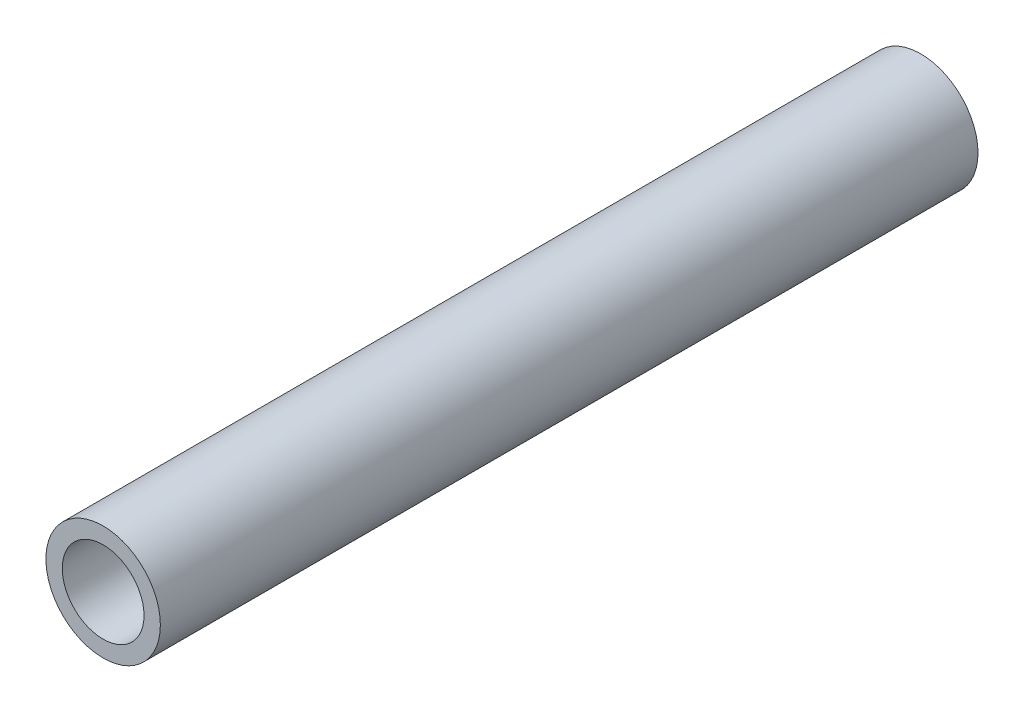
SolidWorks part; units mm, degrees
ref_plane "Plan de face" through (0, 0, 0) normal (0, 0, 1) x (1, 0, 0)
ref_plane "Plan de dessus" through (0, 0, 0) normal (0, 1, 0) x (1, 0, 0)
ref_plane "Plan de droite" through (0, 0, 0) normal (1, 0, 0) x (0, 0, -1)
sketch "Esquisse1" plane through (0, 0, 0) normal (0, 0, 1) x (1, 0, 0)
  circle A0 centre (0, 0) radius 2.5
  circle A1 centre (0, 0) radius 3.5
  dimension "D1" = 5
  dimension "D2" = 5
  dimension "D3" = 7
extrude "Boss.-Extru.1" add sketch "Esquisse1" along normal blind 50
